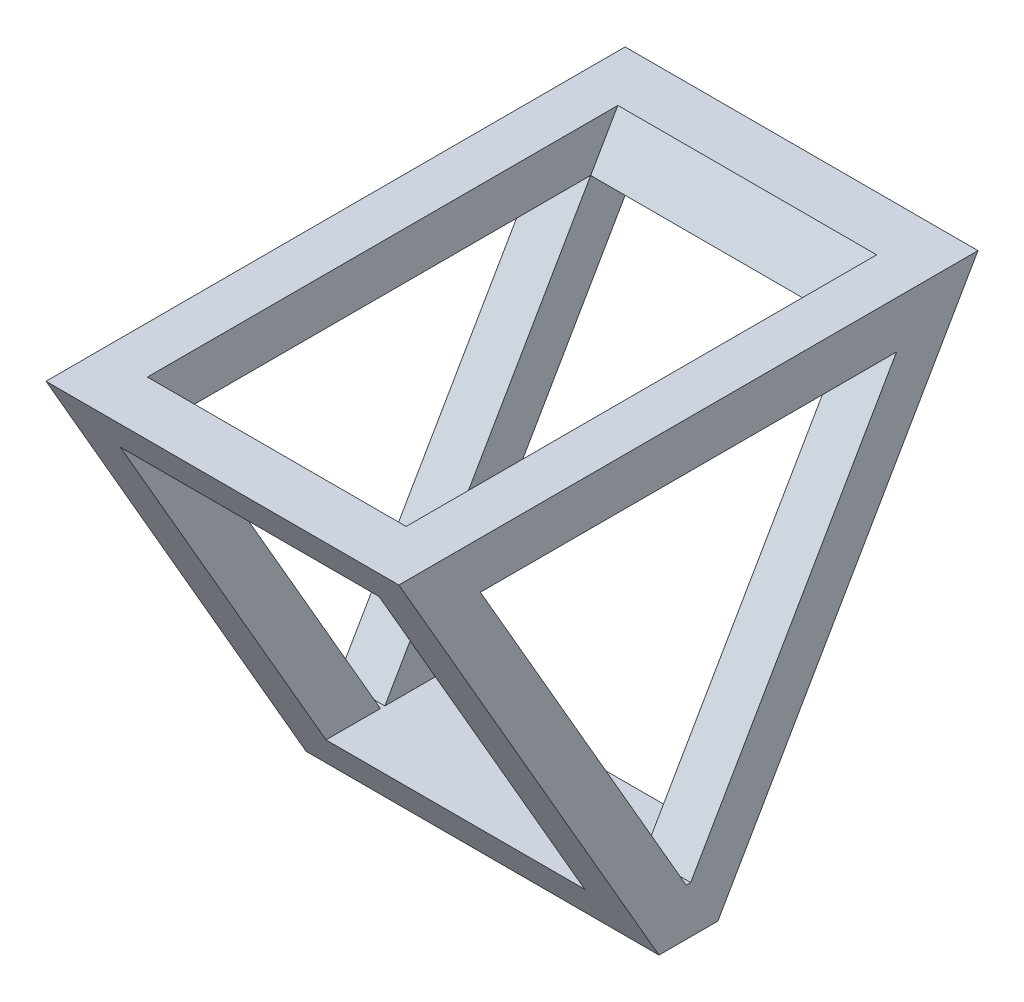
SolidWorks part; units mm, degrees
ref_plane "Front Plane" through (0, 0, 0) normal (0, 0, 1) x (1, 0, 0)
ref_plane "Top Plane" through (0, 0, 0) normal (0, 1, 0) x (1, 0, 0)
ref_plane "Right Plane" through (0, 0, 0) normal (1, 0, 0) x (0, 0, -1)
sketch "Sketch2" plane through (0, 0, 0) normal (1, 0, 0) x (0, 0, -1)
  line L0 (-2.5, 0) -> (2.5, 0)
  line L1 (2.5, 0) -> (24.6188, 38.3109)
  line L2 (24.6188, 38.3109) -> (20, 38.3109)
  line L3 (20, 38.3109) -> (0.1906, 4)
  line L4 (0.1906, 4) -> (-0.1906, 4)
  line L5 (-0.1906, 4) -> (-20, 38.3109)
  line L6 (-20, 38.3109) -> (-24.6188, 38.3109)
  line L7 (-24.6188, 38.3109) -> (-2.5, 0)
  line L8 (0, 4) -> (0, 0) construction
  point P4 (0, 0)
  point P12 (-8.5069, 11.2864)
  point P13 (0, 6.2049)
  point P14 (0, 6.4344)
  point P15 (-11.2916, 13.3786)
  point P16 (-10.6394, 12.9833)
  dimension "D1" = 5
  dimension "D2" = 4
  dimension "D3" = 4
  dimension "D4" = 40
  dimension "D5" = 120
extrude "Boss-Extrude2" add sketch "Sketch2" along normal blind 30
sketch "Sketch3" plane through (0, 0, 0) normal (0, 0, 1) x (1, 0, 0)
  line L0 (0, 10.0462) -> (4, 10.0462) construction
  line L1 (4, 34.3109) -> (26, 34.3109)
  line L2 (4, 34.3109) -> (4, 4)
  line L3 (4, 4) -> (26, 4)
  line L4 (26, 34.3109) -> (26, 4)
  line L5 (0, 38.3109) -> (0, 0) construction
  line L6 (26, 10.0462) -> (30, 10.0462) construction
  line L7 (30, 38.3109) -> (30, 0) construction
  line L8 (30, 38.3109) -> (0, 38.3109) construction
  line L9 (30, 0) -> (0, 0) construction
  dimension "D1" = 4
  dimension "D2" = 4
  dimension "D3" = 4
extrude "Cut-Extrude1" cut sketch "Sketch3" against normal through all both and the other way through all
sketch "Sketch4" plane through (0, 0, 0) normal (0, 0, 1) x (1, 0, 0)
  line L0 (30, 38.3109) -> (0, 38.3109) construction
  line L1 (0, 38.3109) -> (4, 38.3109)
  line L2 (0, 38.3109) -> (0, 34.3109)
  line L3 (0, 34.3109) -> (4, 34.3109)
  line L4 (4, 38.3109) -> (4, 34.3109)
  line L5 (26, 34.3109) -> (30, 34.3109)
  line L6 (26, 34.3109) -> (26, 38.3109)
  line L7 (26, 38.3109) -> (30, 38.3109)
  line L8 (30, 34.3109) -> (30, 38.3109)
  line L10 (30, 0) -> (30, 38.3109) construction
  line L11 (0, 0) -> (0, 38.3109) construction
  line L12 (4, 34.3109) -> (4, 4) construction
  line L13 (26, 4) -> (26, 34.3109) construction
  point P14 (0, 0)
  point P17 (0, 0)
extrude "Boss-Extrude3" add sketch "Sketch4" along normal up to surface and the other way up to surface up to face at (15, 20.1554, 9.5179) other way up to face at (15, 20.1554, -9.5179)
